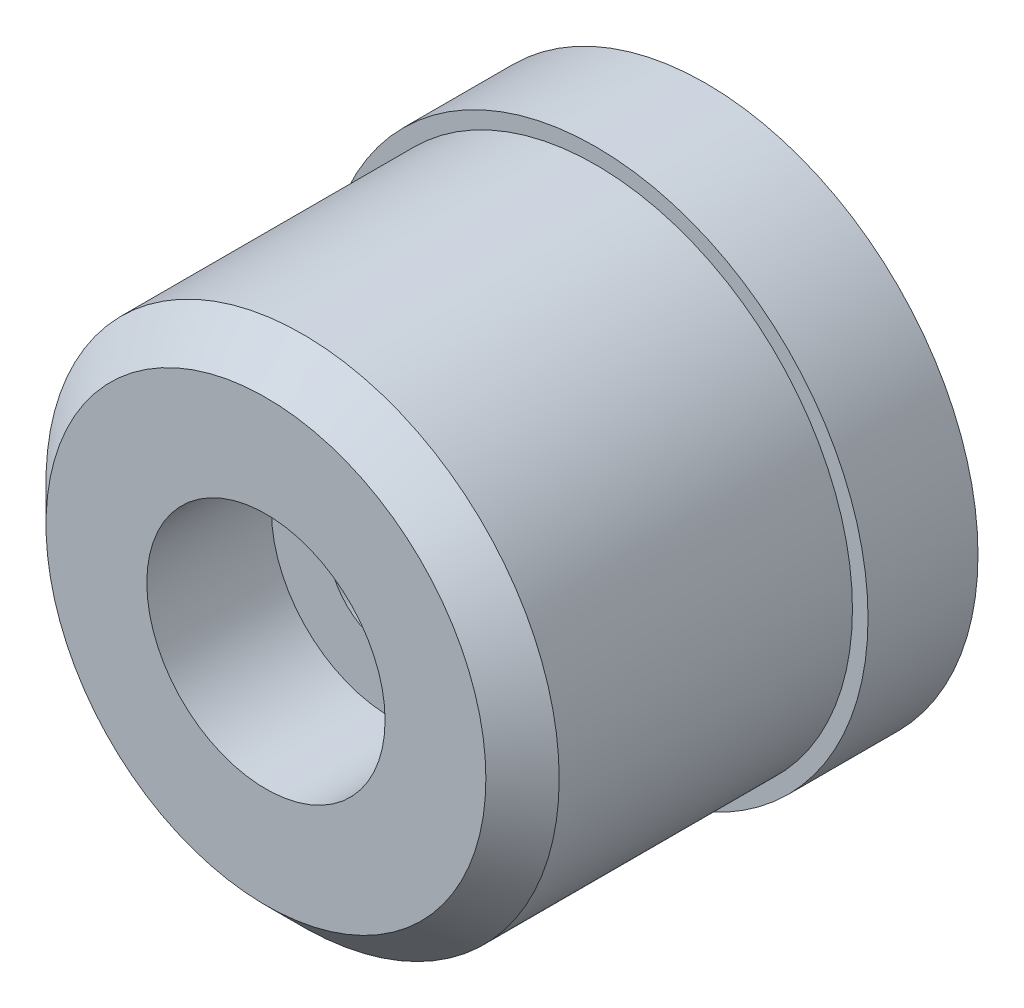
SolidWorks part; units mm, degrees
material "研磨黑纤"
ref_plane "前视基准面" through (0, 0, 0) normal (0, 0, 1) x (1, 0, 0)
ref_plane "上视基准面" through (0, 0, 0) normal (0, 1, 0) x (1, 0, 0)
ref_plane "右视基准面" through (0, 0, 0) normal (1, 0, 0) x (0, 0, -1)
sketch "草图1" plane through (0, 0, 0) normal (0, 0, 1) x (1, 0, 0)
  circle A0 centre (0, 0) radius 7.425
  dimension "D1" = 14.85
extrude "凸台-拉伸1" add sketch "草图1" along normal blind 3
sketch "草图2" plane through (0, 0, 0) normal (0, 0, 1) x (1, 0, 0)
  circle A0 centre (0, 0) radius 7
  dimension "D1" = 14
extrude "凸台-拉伸2" add sketch "草图2" along normal blind 12
hole_wizard "M3 六角凹头螺钉的柱形沉头孔1" positions "草图3" profile "草图4" counterbore size "M3" standard "ISO" end condition through all
sketch "草图3" plane through (0, 0, 12) normal (0, 0, -1) x (-1, 0, 0)
  point P25 (0, 0)
sketch "草图4" plane through (0, 0, 12) normal (1, 0, 0) x (0, -1, 0)
  line L0 (0, 0) -> (0, 12)
  line L1 (0, 12) -> (1.7, 12)
  line L3 (1.7, 12) -> (1.7, 3.4)
  line L4 (1.7, 3.4) -> (3.25, 3.4)
  line L5 (3.25, 3.4) -> (3.25, 0)
  line L7 (3.25, 0) -> (0, 0)
  line L11 (0, -6.35) -> (0, 107.95) construction
  dimension "通孔孔直径" = 3.4
  dimension "通孔孔深度" = 12
  dimension "柱形沉头孔直径" = 6.5
  dimension "柱形沉头孔深度" = 3.4
chamfer "倒角1" distance 1 angle 45 1 edges at (7, 0, 12)
